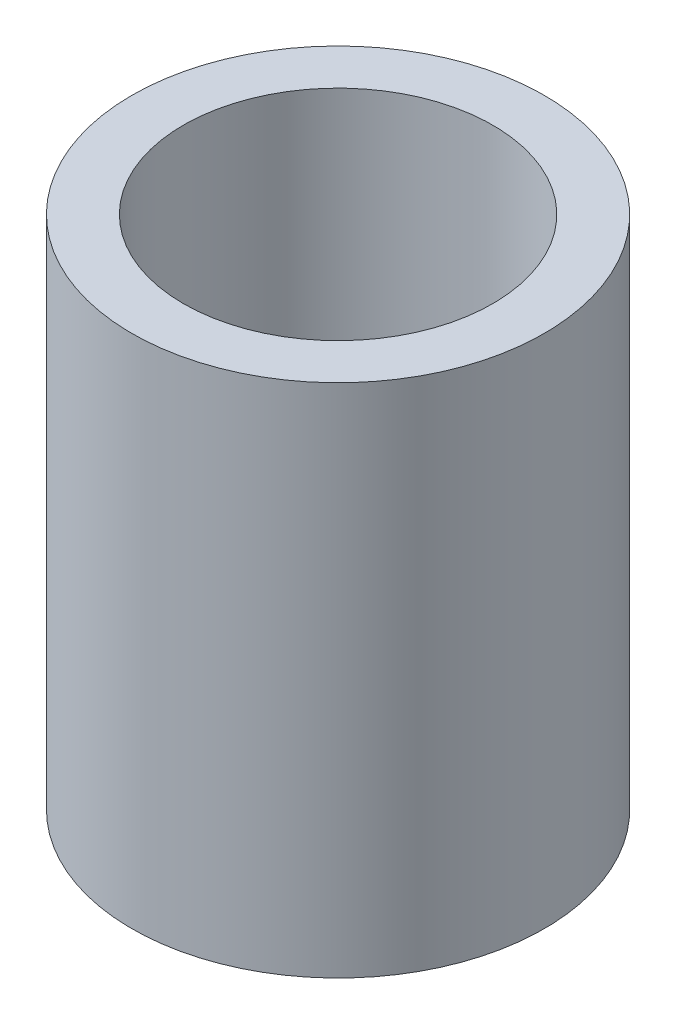
SolidWorks part; units mm, degrees
ref_plane "前基準面" through (0, 0, 0) normal (0, 0, 1) x (1, 0, 0)
ref_plane "上基準面" through (0, 0, 0) normal (0, 1, 0) x (1, 0, 0)
ref_plane "右基準面" through (0, 0, 0) normal (1, 0, 0) x (0, 0, -1)
sketch "草圖3" plane through (0, 0, 0) normal (0, 0, 1) x (1, 0, 0)
  line L0 (0, -16.2609) -> (0, -26.2609)
  line L1 (0, -16.2609) -> (-4, -16.2609)
  line L2 (-4, -16.2609) -> (-4, -26.2609)
  line L3 (-4, -26.2609) -> (0, -26.2609)
revolve "旋轉1" add sketch "草圖3" angle 360 about L0
sketch "草圖4" plane through (0, 0, 0) normal (0, 1, 0) x (1, 0, 0)
  line L0 (0, 0) -> (-2.9995, 0)
  line L1 (-2.9995, 0) -> (3.0005, 0)
  arc A0 (3.0005, 0) -> (-2.9995, 0) centre (0.0005, 0) cw
  arc A1 (3.0005, 0) -> (-2.9995, 0) centre (0.0005, 0) ccw
extrude "除料-伸長1" cut sketch "草圖4" against normal blind 25 contours A0 L1 L0 | L1 A1 L0
